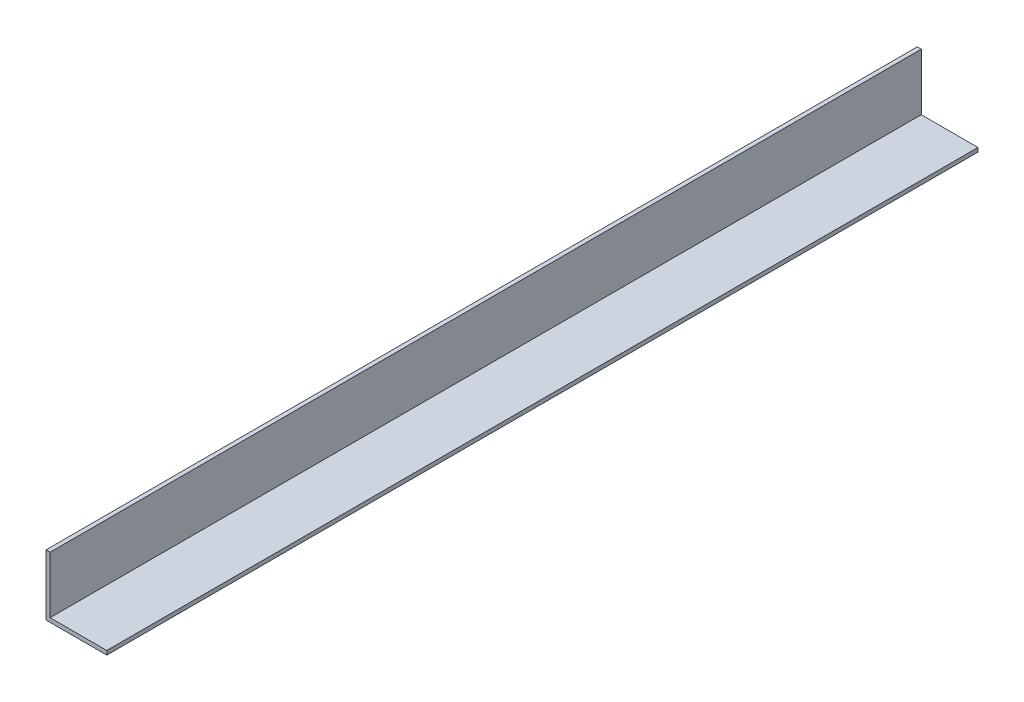
SolidWorks part; units mm, degrees
material "1060 Alloy"
ref_plane "Front Plane" through (0, 0, 0) normal (0, 0, 1) x (1, 0, 0)
ref_plane "Top Plane" through (0, 0, 0) normal (0, 1, 0) x (1, 0, 0)
ref_plane "Right Plane" through (0, 0, 0) normal (1, 0, 0) x (0, 0, -1)
sketch "Sketch1" plane through (0, 0, 0) normal (0, 0, 1) x (1, 0, 0)
  line L0 (0, 5.6023) -> (0, 35.6023)
  line L1 (0, 35.6023) -> (2, 35.6023)
  line L2 (2, 35.6023) -> (2, 7.6023)
  line L3 (2, 7.6023) -> (30, 7.6023)
  line L4 (30, 7.6023) -> (30, 5.6023)
  line L5 (30, 5.6023) -> (0, 5.6023)
extrude "Boss-Extrude1" add sketch "Sketch1" along normal blind 410 and the other way up to vertex (20 mm away)
